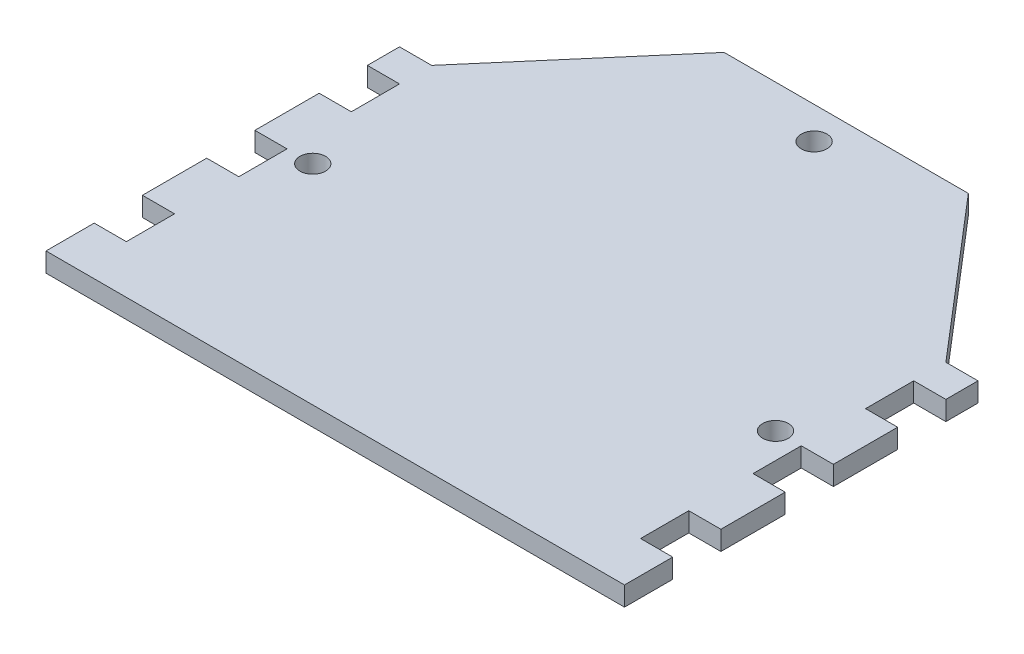
SolidWorks part; units mm, degrees
ref_plane "Front Plane" through (0, 0, 0) normal (0, 0, 1) x (1, 0, 0)
ref_plane "Top Plane" through (0, 0, 0) normal (0, 1, 0) x (1, 0, 0)
ref_plane "Right Plane" through (0, 0, 0) normal (1, 0, 0) x (0, 0, -1)
sketch "Sketch1" plane through (0, 0, 0) normal (0, 1, 0) x (1, 0, 0)
  line L0 (72.9688, 0) -> (0, 0) construction
  line L1 (0, 54.3862) -> (0, -48.3135) construction
  line L2 (40, 10.5) -> (-63.7742, 10.5) construction
  line L3 (28, -33) -> (71.3405, -33) construction
  line L4 (-19, 35) -> (-40, 10.5)
  line L5 (19, 35) -> (-19, 35)
  line L6 (-40, 10.5) -> (-45, 10.5)
  line L7 (-19, 10.2379) -> (-19, 43.7621) construction
  line L8 (19, 27) -> (19, 35) construction
  line L10 (19, 35) -> (40, 10.5)
  line L11 (-40, -29.5) -> (-40, -37)
  line L12 (-40, -44.5) -> (40, -44.5)
  line L13 (-36, 29) -> (-36, 35) construction
  line L14 (36, 11.9309) -> (36, -51.3384) construction
  line L15 (10.086, -33) -> (25.5, -33) construction
  line L16 (28, -33) -> (44, -33) construction
  line L17 (-45, 10.5) -> (-45, 5.5)
  line L18 (40, -37) -> (45, -37)
  line L19 (-45, -44.5) -> (-40, -44.5)
  line L20 (45, -29.5) -> (40, -29.5)
  line L21 (-40, -12) -> (-40, -19.5)
  line L22 (40, -19.5) -> (45, -19.5)
  line L23 (-40, 5.5) -> (-40, -2)
  line L24 (40, -12) -> (45, -12)
  line L25 (-45, -37) -> (-45, -44.5)
  line L26 (-45, -19.5) -> (-45, -29.5)
  line L27 (-40, 5.5) -> (-45, 5.5)
  line L28 (45, -2) -> (40, -2)
  line L30 (40, 5.5) -> (45, 5.5)
  line L31 (-45, -2) -> (-40, -2)
  line L32 (-40, -12) -> (-45, -12)
  line L33 (-45, -2) -> (-45, -12)
  line L34 (-40, -19.5) -> (-45, -19.5)
  line L35 (-45, -29.5) -> (-40, -29.5)
  line L36 (-40, -37) -> (-45, -37)
  line L40 (45, -37) -> (45, -44.5)
  line L41 (45, -44.5) -> (40, -44.5)
  line L43 (40, -37) -> (40, -29.5)
  line L45 (45, -29.5) -> (45, -19.5)
  line L47 (40, -12) -> (40, -19.5)
  line L48 (45, -12) -> (45, -2)
  line L49 (40, 5.5) -> (40, -2)
  line L50 (40, 10.5) -> (45, 10.5)
  line L51 (45, 10.5) -> (45, 5.5)
  circle A2 centre (-36, -12) radius 2
  circle A3 centre (36, -12) radius 2
  circle A4 centre (0, 30) radius 2
  point P27 (-19, 27)
  point P36 (15, -33)
  point P44 (42.5, -29.5)
  point P52 (42.5, -12)
  dimension "D6" = 7.5
  dimension "D7" = 12
  dimension "D8" = 12
  dimension "D9" = 5
  dimension "D11" = 16
  dimension "D13" = 10
  dimension "D2" = 36
  dimension "D1" = 35
  dimension "D10" = 7.5
  dimension "D12" = 8
  dimension "D14" = 7.5
  dimension "D15" = 10
  dimension "D16" = 7.5
  dimension "D17" = 55
extrude "Boss-Extrude1" add sketch "Sketch1" along normal blind 3
